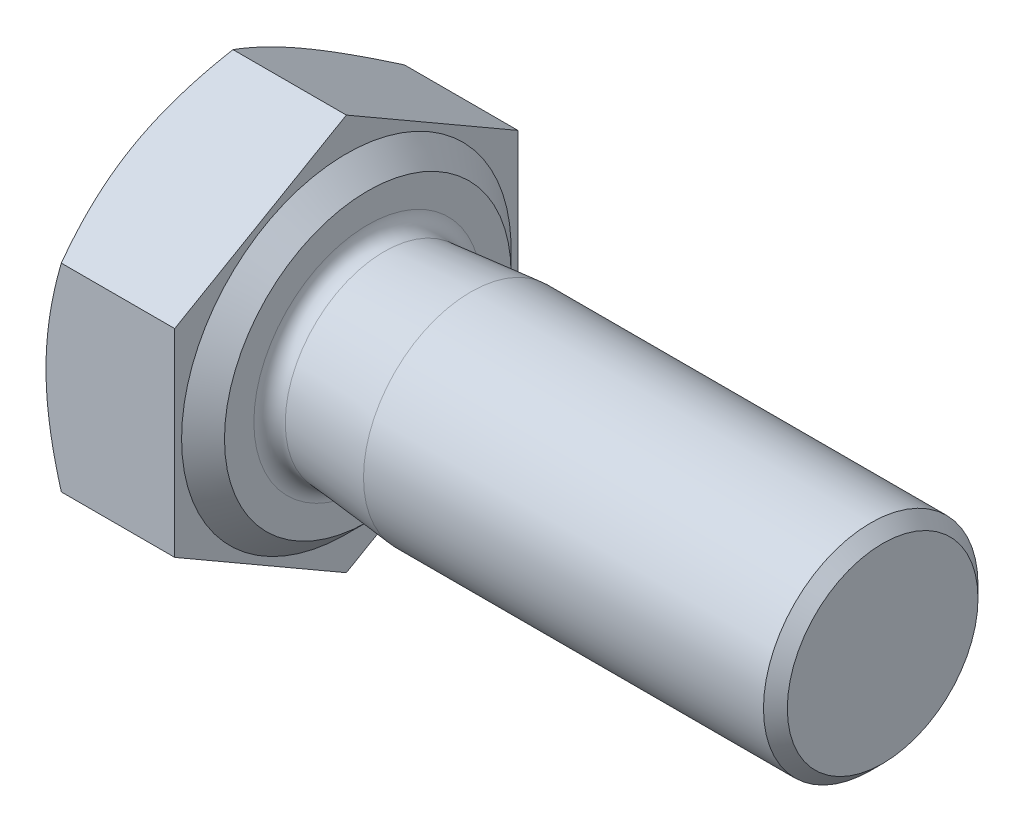
SolidWorks part; units mm, degrees
ref_plane "前视基准面" through (0, 0, 0) normal (0, 0, 1) x (1, 0, 0)
ref_plane "上视基准面" through (0, 0, 0) normal (0, 1, 0) x (1, 0, 0)
ref_plane "右视基准面" through (0, 0, 0) normal (1, 0, 0) x (0, 0, -1)
sketch "草图1" plane through (0, 0, 0) normal (0, 0, 1) x (1, 0, 0)
  line L0 (0, 0) -> (15.5, 0) construction
  line L1 (0, 0) -> (0, 4.395)
  line L2 (0, 4.395) -> (3.5, 4.395)
  line L3 (3.5, 4.395) -> (3.5, 0)
  line L4 (3.5, 2.5) -> (15.5, 2.5)
  line L5 (15.5, 2.5) -> (15.5, 0)
  line L6 (0, 4) -> (0.2281, 4.395)
  line L7 (14.3, 2.5) -> (14.3, 0)
  line L8 (5.9, 2.5) -> (5.9, 0)
  line L9 (3.5, 2.3051) -> (15.5, 2.3051)
  line L10 (15.5, 2.1752) -> (3.5, 2.1752)
  line L11 (3, 3.84) -> (3.5, 3.34)
  line L12 (3, 4.395) -> (3, 0)
  line L13 (3.4, 3.44) -> (3.4, 0) construction
  arc A0 (3.5, 2.85) -> (3.85, 2.5) centre (3.85, 2.85) ccw
  point P12 (14.9, 0)
  point P13 (1.15, 4.395)
  point P14 (3.5, 2.85)
  point P24 (3.5, 3.44)
  dimension "D1" = 0.1
  dimension "r" = 0.35
  dimension "k" = 3.5
  dimension "D2" = 45
  dimension "β" = 30
  dimension "e" = 8.79
  dimension "s" = 8
  dimension "d" = 5
  dimension "l" = 12
  dimension "D52" = 1.2
  dimension "P" = 0.6
  dimension "kw" = 2.35
  dimension "da" = 5.7
  dimension "a" = 2.4
  dimension "ds" = 4.6103
  dimension "D61" = 4.3505
  dimension "dw" = 6.88
  dimension "c" = 0.5
sketch "草图2" plane through (0, 0, 0) normal (1, 0, 0) x (0, 0, -1)
  line L1 (0, 4.6188) -> (-4, 2.3094)
  line L2 (-4, 2.3094) -> (-4, -2.3094)
  line L3 (-4, -2.3094) -> (0, -4.6188)
  line L4 (0, -4.6188) -> (4, -2.3094)
  line L5 (4, -2.3094) -> (4, 2.3094)
  line L6 (4, 2.3094) -> (0, 4.6188)
  circle A0 centre (0, 0) radius 4 construction
sketch "草图3" plane through (0, 0, 0) normal (1, 0, 0) x (0, 0, -1)
  line L0 (4, 2.3094) -> (0, 4.6188) construction
  line L1 (0, 4.6188) -> (-4, 2.3094) construction
  line L2 (-4, 2.3094) -> (-4, -2.3094) construction
  line L3 (4, -2.3094) -> (4, 2.3094) construction
  line L4 (0, -4.6188) -> (4, -2.3094) construction
  line L5 (-4, -2.3094) -> (0, -4.6188) construction
  line L6 (4, 2.3094) -> (0, 4.6188)
  line L7 (0, 4.6188) -> (-4, 2.3094)
  line L8 (-4, 2.3094) -> (-4, -2.3094)
  line L9 (4, -2.3094) -> (4, 2.3094)
  line L10 (0, -4.6188) -> (4, -2.3094)
  line L11 (-4, -2.3094) -> (0, -4.6188)
extrude "凸台-拉伸1" add sketch "草图3" along normal up to vertex (3.5 mm away) up to point (3.5, 4.395, 0)
sketch "草图4" plane through (0, 0, 0) normal (-1, 0, 0) x (0, 0, 1)
  circle A0 centre (0, 0) radius 4 construction
  circle A1 centre (0, 0) radius 4
  circle A2 centre (0, 0) radius 8.79
  dimension "D1" = 17.58
extrude "切除-拉伸1" cut sketch "草图4" against normal blind 0.4375 draft 60
sketch "草图5" [suppressed] plane through (0, 0, 0) normal (0, 0, 1) x (1, 0, 0)
  line L0 (33, 26) -> (233, 26) construction
  line L1 (233, 26) -> (233, 0) construction
  line L2 (0, 0) -> (233, 0) construction
  line L3 (35.3, 26) -> (233, 26)
  line L4 (233, 26) -> (233, 0)
  line L5 (33, 0) -> (233, 0)
  line L6 (33, 28.3) -> (33, 0)
  arc A0 (33, 28.3) -> (35.3, 26) centre (35.3, 28.3) ccw construction
  arc A1 (33, 28.3) -> (35.3, 26) centre (35.3, 28.3) ccw
revolve "旋转1" [suppressed] add sketch "草图5" angle 360 about L5
cosmetic thread "装饰螺纹线2" [suppressed] parameters "D1"=9.6, "D2"=4.3505
chamfer "倒角2" [suppressed] distance 0.2778 angle 45
sketch "草图7" [suppressed] plane through (0, 0, 0) normal (0, 0, 1) x (1, 0, 0)
  line L0 (33, 37) -> (32, 38)
  line L1 (32, 38) -> (32, 88.25)
  line L2 (32, 88.25) -> (33, 88.25)
  line L3 (33, 88.25) -> (33, 37)
  line L4 (0, 0) -> (233, 0) construction
  line L5 (0, 0) -> (233, 0) construction
  dimension "D1" = 17.58
revolve "切除-旋转1" [suppressed] cut sketch "草图7" angle 360 mid plane about L5
sketch "草图6" plane through (0, 0, 0) normal (0, 0, 1) x (1, 0, 0)
  line L0 (5.9, 0) -> (5.9, 2.5) construction
  line L1 (5.9, 2.5) -> (15.5, 2.5)
  line L2 (15.5, 2.5) -> (15.5, 0)
  line L3 (5.9, 2.5) -> (3.8834, 2.3067)
  line L5 (3.5, 2.3051) -> (15.5, 2.3051) construction
  line L6 (3.5, 4.395) -> (3.5, 0) construction
  line L7 (3.5, 2.6552) -> (3.5, 0)
  line L8 (3.5, 0) -> (15.5, 0)
  arc A0 (3.8834, 2.3067) -> (3.5, 2.6552) centre (3.85, 2.6552) cw
  arc A1 (3.5, 2.85) -> (3.85, 2.5) centre (3.85, 2.85) ccw construction
revolve "旋转2" add sketch "草图6" angle 360 about L8
cosmetic thread "装饰螺纹线1" parameters "D1"=9.6, "D2"=4.3505
chamfer "倒角1" distance 0.2778 angle 45 1 edges at (15.5, 0, 2.5)
sketch "草图8" plane through (0, 0, 0) normal (0, 0, 1) x (1, 0, 0)
  line L0 (3.5, 3.34) -> (3, 3.84)
  line L1 (3, 3.84) -> (3, 8.79)
  line L2 (3, 8.79) -> (3.5, 8.79)
  line L3 (3.5, 8.79) -> (3.5, 3.34)
  line L4 (0, 0) -> (15.5, 0) construction
  line L5 (0, 0) -> (15.5, 0) construction
  dimension "D1" = 17.58
revolve "切除-旋转2" cut sketch "草图8" angle 360 mid plane about L5
